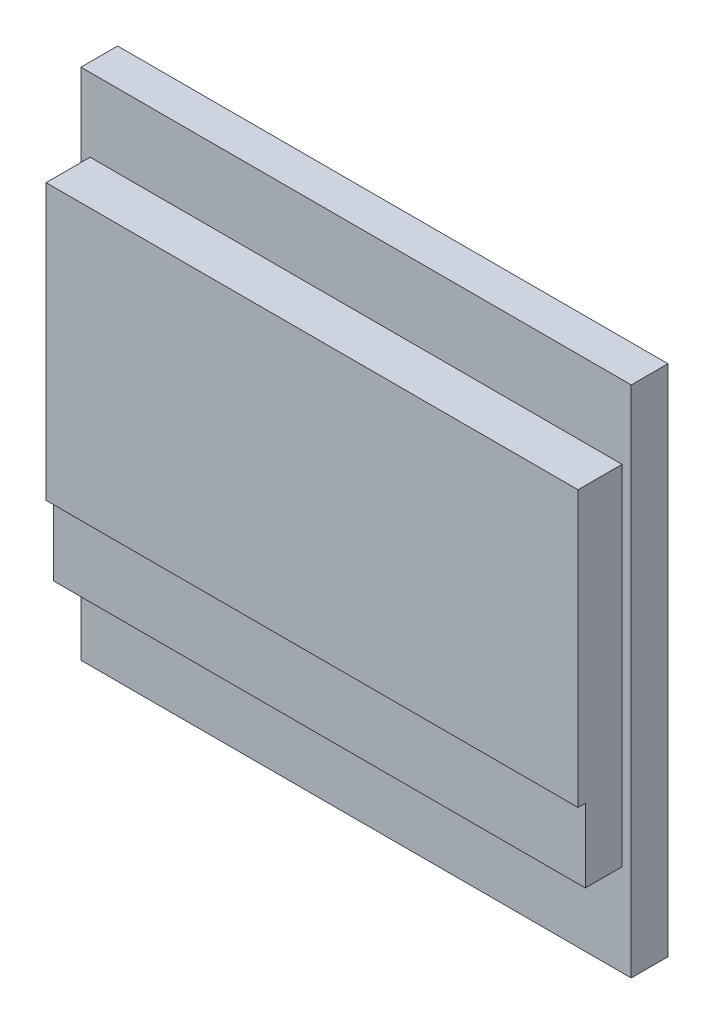
SolidWorks part; units mm, degrees
ref_plane "前视基准面" through (0, 0, 0) normal (0, 0, 1) x (1, 0, 0)
ref_plane "上视基准面" through (0, 0, 0) normal (0, 1, 0) x (1, 0, 0)
ref_plane "右视基准面" through (0, 0, 0) normal (1, 0, 0) x (0, 0, -1)
sketch "草图1" plane through (0, 0, 0) normal (0, 0, 1) x (1, 0, 0)
  line L1 (-15, -14) -> (15, -14)
  line L2 (-15, -14) -> (-15, 14)
  line L3 (-15, 14) -> (15, 14)
  line L4 (15, -14) -> (15, 14)
  line L5 (-15, -14) -> (15, 14) construction
  line L6 (-15, 14) -> (15, -14) construction
  point P0 (0, 0)
  dimension "D1" = 30
  dimension "D2" = 28
sketch "草图2" plane through (0, 0, 0) normal (0, 0, 1) x (1, 0, 0)
  line L0 (-1000, 0) -> (49000, 0) construction
  line L1 (0, -1000) -> (0, 49000) construction
  line L2 (-14.5, 10) -> (14.5, 10)
  line L3 (-15, 14) -> (15, 14) construction
  line L4 (-14.5, 10) -> (-14.5, -9)
  line L5 (-14.5, -9) -> (14.5, -9)
  line L6 (14.5, -9) -> (14.5, 10)
  point P8 (0, 10)
  dimension "D1" = 4
  dimension "D2" = 29
  dimension "D3" = 19
sketch "草图3" plane through (0, 0, 0) normal (0, 0, 1) x (1, 0, 0)
  line L0 (14.5, -9) -> (14.5, 10) construction
  line L1 (-14.5, 10) -> (14.5, 10)
  line L2 (-14.5, 10) -> (-14.5, -5)
  line L3 (-14.5, -5) -> (14.5, -5)
  line L4 (14.5, 10) -> (14.5, -5)
  dimension "D1" = 15
extrude "凸台-拉伸1" add sketch "草图1" against normal blind 2
extrude "凸台-拉伸2" add sketch "草图2" along normal blind 2 contours L2 L6 L5 L4
extrude "凸台-拉伸3" add sketch "草图3" along normal blind 2.4
